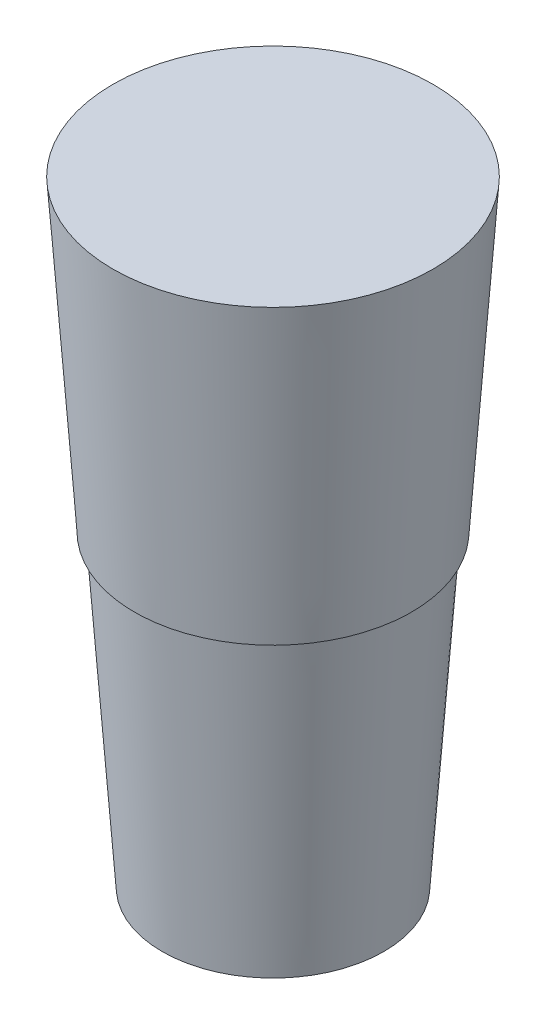
SolidWorks part; units mm, degrees
ref_plane "Front Plane" through (0, 0, 0) normal (0, 0, 1) x (1, 0, 0)
ref_plane "Top Plane" through (0, 0, 0) normal (0, 1, 0) x (1, 0, 0)
ref_plane "Right Plane" through (0, 0, 0) normal (1, 0, 0) x (0, 0, -1)
sketch "Sketch1" plane through (0, 0, 0) normal (0, 0, 1) x (1, 0, 0)
  line L6 (42.0305, -40.6154) -> (64.8905, -40.6154)
  line L7 (64.8905, -40.6154) -> (69.3355, 22.8846)
  line L8 (69.3355, 22.8846) -> (70.6054, 22.8846)
  line L9 (70.6054, 22.8846) -> (75.0505, 86.3846)
  line L10 (75.0505, 86.3846) -> (42.0305, 86.3846)
  line L11 (42.0305, -40.6154) -> (42.0305, 86.3846)
  dimension "D1" = 22.86
  dimension "D2" = 63.5
  dimension "D3" = 63.5
  dimension "D4" = 1.27
  dimension "D5" = 10.16
revolve "Revolve1" add sketch "Sketch1" angle 360 about L11
